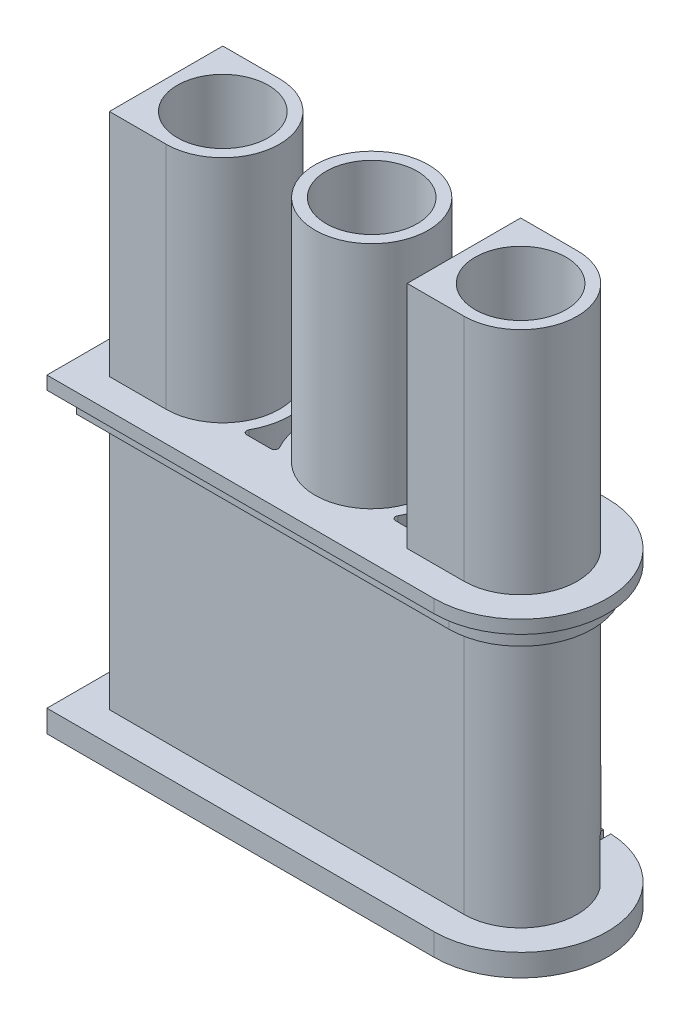
SolidWorks part; units mm, degrees
material "Nylon 6/10"
ref_plane "Front Plane" through (0, 0, 0) normal (0, 0, 1) x (1, 0, 0)
ref_plane "Top Plane" through (0, 0, 0) normal (0, 1, 0) x (1, 0, 0)
ref_plane "Right Plane" through (0, 0, 0) normal (1, 0, 0) x (0, 0, -1)
sketch "Sketch1" plane through (0, 0, 0) normal (0, 1, 0) x (1, 0, 0)
  line L0 (-10.06, 0) -> (10.06, 0) construction
  line L1 (-10.06, 3.83) -> (-13.89, 3.83)
  line L2 (-13.89, 3.83) -> (-13.89, -3.83)
  line L3 (-13.89, -3.83) -> (-10.06, -3.83)
  line L4 (10.06, 3.83) -> (6.23, 3.83)
  line L5 (6.23, 3.83) -> (6.23, -3.83)
  line L6 (6.23, -3.83) -> (10.06, -3.83)
  circle A0 centre (-10.06, 0) radius 3.075
  circle A1 centre (0, 0) radius 3.075
  circle A2 centre (10.06, 0) radius 3.075
  circle A3 centre (0, 0) radius 3.83
  arc A4 (-10.06, -3.83) -> (-10.06, 3.83) centre (-10.06, 0) ccw
  arc A5 (10.06, -3.83) -> (10.06, 3.83) centre (10.06, 0) ccw
  point P8 (-6.23, 0)
  point P9 (-3.83, 0)
  point P18 (13.89, 0)
  dimension "D2" = 6.15
  dimension "D1" = 7.66
  dimension "D3" = 2.4
  dimension "D4" = 27.78
extrude "Boss-Extrude1" add sketch "Sketch1" along normal blind 36.5
sketch "Sketch2" plane through (0, 0, 0) normal (0, 1, 0) x (1, 0, 0)
  line L0 (-10.06, 0) -> (10.06, 0) construction
  line L1 (-10.06, 5.85) -> (10.06, 5.85)
  line L2 (-10.06, -5.85) -> (10.06, -5.85)
  line L3 (-10.06, -5.85) -> (-16.09, -5.85)
  line L4 (-16.09, -5.85) -> (-16.09, 5.85)
  line L5 (-16.09, 5.85) -> (-10.06, 5.85)
  line L12 (5.485, -2.6) -> (5.485, 2.6)
  line L13 (5.485, 2.6) -> (3.7644, 2.6)
  line L14 (-3.7644, 2.6) -> (-6.2956, 2.6)
  line L15 (3.7644, -2.6) -> (5.485, -2.6)
  line L16 (-6.2956, -2.6) -> (-3.7644, -2.6)
  arc A0 (-10.06, -5.85) -> (-10.06, 5.85) centre (-10.06, 0) cw construction
  arc A1 (10.06, -5.85) -> (10.06, 5.85) centre (10.06, 0) ccw
  circle A2 centre (10.06, 0) radius 3.075 construction
  circle A4 centre (0, 0) radius 3.075 construction
  circle A5 centre (-10.06, 0) radius 3.075 construction
  circle A6 centre (0, 0) radius 3.075 construction
  circle A7 centre (10.06, 0) radius 3.075 construction
  circle A8 centre (0, 0) radius 3.83 construction
  circle A10 centre (-10.06, 0) radius 3.075
  circle A11 centre (0, 0) radius 3.075 construction
  circle A12 centre (0, 0) radius 3.075
  circle A13 centre (10.06, 0) radius 3.075 construction
  circle A14 centre (10.06, 0) radius 3.075
  arc A16 (-10.06, -3.075) -> (-10.06, 3.075) centre (-10.06, 0) ccw construction
  circle A17 centre (0, 0) radius 3.83 construction
  arc A18 (-6.2956, -2.6) -> (-6.2956, 2.6) centre (-10.06, 0) ccw
  arc A19 (-3.7644, 2.6) -> (-3.7644, -2.6) centre (0, 0) ccw
  circle A20 centre (10.06, 0) radius 4.575 construction
  arc A21 (3.7644, -2.6) -> (3.7644, 2.6) centre (0, 0) ccw
  circle A22 centre (0, 0) radius 4.575 construction
  arc A24 (-10.06, -4.575) -> (-10.06, 4.575) centre (-10.06, 0) ccw construction
  point P2 (0, 0)
  point P10 (15.91, 0)
  point P37 (4.575, 0)
  dimension "D1" = 5.85
  dimension "D2" = 32
  dimension "D4" = 5.2
  dimension "D3" = 1.5
extrude "Boss-Extrude2" add sketch "Sketch2" along normal blind 1.5
sketch "Sketch3" plane through (0, 1.5, 0) normal (0, 1, 0) x (1, 0, 0)
  line L0 (-10.06, -3.83) -> (-13.89, -3.83) construction
  line L1 (-13.89, -3.83) -> (-13.89, 3.83) construction
  line L2 (-13.89, 3.83) -> (-10.06, 3.83) construction
  line L3 (6.23, 3.83) -> (10.06, 3.83) construction
  line L4 (10.06, -3.83) -> (6.23, -3.83) construction
  line L5 (-1.3879, -3.83) -> (-13.89, -3.83)
  line L6 (-13.89, -3.83) -> (-13.89, 3.83)
  line L7 (-13.89, 3.83) -> (-3.321, 3.83)
  line L8 (-3.321, 3.83) -> (10.06, 3.83)
  line L9 (10.06, -3.83) -> (-1.3879, -3.83)
  line L13 (-3.7644, 2.6) -> (-6.2956, 2.6)
  line L14 (-6.2956, -2.6) -> (-3.7644, -2.6)
  line L15 (-3.7644, 2.6) -> (-6.2956, 2.6)
  line L16 (-6.2956, -2.6) -> (-3.7644, -2.6)
  line L19 (5.485, -2.6) -> (5.485, 2.6)
  line L20 (3.7644, -2.6) -> (5.485, -2.6)
  line L21 (5.485, 2.6) -> (3.7644, 2.6)
  line L22 (5.485, -2.6) -> (5.485, 2.6)
  line L23 (3.7644, -2.6) -> (5.485, -2.6)
  line L24 (5.485, 2.6) -> (3.7644, 2.6)
  arc A0 (10.06, -3.83) -> (10.06, 3.83) centre (10.06, 0) ccw construction
  arc A1 (10.06, -3.83) -> (10.06, 3.83) centre (10.06, 0) ccw
  circle A2 centre (-10.06, 0) radius 3.075 construction
  arc A3 (3.7644, -2.6) -> (3.7644, 2.6) centre (0, 0) ccw
  arc A4 (-3.7644, 2.6) -> (-3.7644, -2.6) centre (0, 0) ccw
  arc A5 (-6.2956, -2.6) -> (-6.2956, 2.6) centre (-10.06, 0) ccw
  arc A6 (-3.7644, 2.6) -> (-3.7644, -2.6) centre (0, 0) ccw
  arc A7 (-6.2956, -2.6) -> (-6.2956, 2.6) centre (-10.06, 0) ccw
  arc A8 (3.7644, -2.6) -> (3.7644, 2.6) centre (0, 0) ccw
  circle A9 centre (-10.06, 0) radius 3.075
  circle A10 centre (0, 0) radius 3.075 construction
  circle A11 centre (0, 0) radius 3.075
  circle A12 centre (10.06, 0) radius 3.075 construction
  circle A13 centre (10.06, 0) radius 3.075
  dimension "D1" = 0
  dimension "D2" = 0
extrude "Boss-Extrude3" add sketch "Sketch3" along normal blind 17.2
sketch "Sketch4" plane through (0, 18.7, 0) normal (0, 1, 0) x (1, 0, 0)
  line L2 (-3.7644, 2.6) -> (-6.2956, 2.6)
  line L3 (-6.2956, -2.6) -> (-3.7644, -2.6)
  line L4 (-3.7644, 2.6) -> (-6.2956, 2.6)
  line L5 (10.06, 5.85) -> (-10.06, 5.85)
  line L6 (-10.06, -5.85) -> (10.06, -5.85)
  line L7 (-16.09, -5.85) -> (-10.06, -5.85)
  line L8 (-16.09, 5.85) -> (-16.09, -5.85)
  line L9 (-10.06, 5.85) -> (-16.09, 5.85)
  line L10 (10.06, 5.85) -> (-10.06, 5.85)
  line L11 (-10.06, -5.85) -> (10.06, -5.85)
  line L12 (-16.09, -5.85) -> (-10.06, -5.85)
  line L13 (-16.09, 5.85) -> (-16.09, -5.85)
  line L14 (-10.06, 5.85) -> (-16.09, 5.85)
  line L15 (-6.2956, -2.6) -> (-3.7644, -2.6)
  line L17 (5.485, -2.6) -> (5.485, 2.6)
  line L18 (5.485, 2.6) -> (3.7644, 2.6)
  line L19 (3.7644, -2.6) -> (5.485, -2.6)
  line L20 (5.485, -2.6) -> (5.485, 2.6)
  line L21 (5.485, 2.6) -> (3.7644, 2.6)
  line L22 (3.7644, -2.6) -> (5.485, -2.6)
  circle A1 centre (-10.06, 0) radius 3.075
  circle A2 centre (-10.06, 0) radius 3.075
  arc A3 (10.06, -5.85) -> (10.06, 5.85) centre (10.06, 0) ccw
  arc A4 (10.06, -5.85) -> (10.06, 5.85) centre (10.06, 0) ccw
  circle A5 centre (10.06, 0) radius 3.075
  circle A6 centre (10.06, 0) radius 3.075
  circle A7 centre (0, 0) radius 3.075
  circle A8 centre (0, 0) radius 3.075
  arc A9 (3.7644, -2.6) -> (3.7644, 2.6) centre (0, 0) ccw
  arc A10 (-6.2956, -2.6) -> (-6.2956, 2.6) centre (-10.06, 0) ccw
  arc A11 (-3.7644, 2.6) -> (-3.7644, -2.6) centre (0, 0) ccw
  arc A12 (-6.2956, -2.6) -> (-6.2956, 2.6) centre (-10.06, 0) ccw
  arc A13 (-3.7644, 2.6) -> (-3.7644, -2.6) centre (0, 0) ccw
  arc A14 (3.7644, -2.6) -> (3.7644, 2.6) centre (0, 0) ccw
  dimension "D1" = 0
  dimension "D2" = 0
  dimension "D3" = 0
  dimension "D4" = 0
  dimension "D5" = 0
  dimension "D6" = 0
extrude "Boss-Extrude4" add sketch "Sketch4" along normal blind 2.29
sketch "Sketch5" plane through (0, 18.7, 0) normal (0, -1, 0) x (1, 0, 0)
  line L0 (-16.09, 5.85) -> (10.06, 5.85) construction
  line L1 (10.06, -5.85) -> (-16.09, -5.85) construction
  line L2 (-16.09, -5.85) -> (-16.09, 5.85) construction
  line L3 (-16.09, 5.85) -> (10.06, 5.85)
  line L4 (10.06, -5.85) -> (-16.09, -5.85)
  line L5 (-16.09, -5.85) -> (-16.09, 5.85)
  line L6 (-15.09, 4.85) -> (10.06, 4.85)
  line L7 (10.06, -4.85) -> (-15.09, -4.85)
  line L8 (-15.09, -4.85) -> (-15.09, 4.85)
  arc A0 (10.06, -5.85) -> (10.06, 5.85) centre (10.06, 0) ccw construction
  arc A1 (10.06, -5.85) -> (10.06, 5.85) centre (10.06, 0) ccw
  arc A2 (10.06, -4.85) -> (10.06, 4.85) centre (10.06, 0) ccw
  dimension "D1" = 1
extrude "Cut-Extrude1" cut sketch "Sketch5" against normal blind 1.4
fillet "Fillet1" radius 0.25 8 edges at (5.485, 10.495, 2.6) (-3.7644, 10.495, 2.6) (-3.7644, 10.495, -2.6) (5.485, 10.495, -2.6) (3.7644, 10.495, -2.6) (3.7644, 10.495, 2.6) (-6.2956, 10.495, 2.6) (-6.2956, 10.495, -2.6)
sketch "Sketch6" plane through (0, 0, 0) normal (0, -1, 0) x (1, 0, 0)
  line L0 (-10.06, 0) -> (-10.06, -6.7468)
  line L1 (-10.06, -6.7468) -> (10.06, -7.1811)
  line L2 (10.06, -7.1811) -> (10.06, 0)
  circle A0 centre (10.06, 0) radius 3.075 construction
  circle A1 centre (-10.06, 0) radius 3.075 construction
extrude "Cut-Extrude-Thin2" cut sketch "Sketch6" against normal blind 1.6 thin thin type mid plane wall 0.5
sketch "Sketch7" plane through (0, 1.5, 0) normal (0, 1, 0) x (1, 0, 0)
  line L0 (-13.135, 8.7382) -> (-6.985, 8.7382)
  line L1 (-13.135, 8.7382) -> (-13.135, 0)
  line L2 (-6.985, 8.7382) -> (-6.985, 0)
  line L3 (-13.135, 0) -> (-6.985, 0)
  line L4 (-13.135, 8.7382) -> (-6.985, 0) construction
  line L5 (-6.985, 8.7382) -> (-13.135, 0) construction
  line L6 (6.985, 8.359) -> (6.985, 0)
  line L7 (6.985, 8.359) -> (13.135, 8.359)
  line L8 (6.985, 0) -> (13.135, 0)
  line L9 (13.135, 8.359) -> (13.135, 0)
  line L10 (6.985, 8.359) -> (13.135, 0) construction
  line L11 (6.985, 0) -> (13.135, 8.359) construction
  arc A0 (9.81, 3.0648) -> (10.31, 3.0648) centre (10.06, 0) ccw construction
  arc A1 (-10.31, 3.0648) -> (-9.81, 3.0648) centre (-10.06, 0) ccw construction
  point P0 (10.06, 0)
  point P1 (-10.06, 4.3691)
  point P2 (10.06, 4.1795)
  point P14 (-10.06, 0)
extrude "Cut-Extrude2" cut sketch "Sketch7" along normal blind 3
